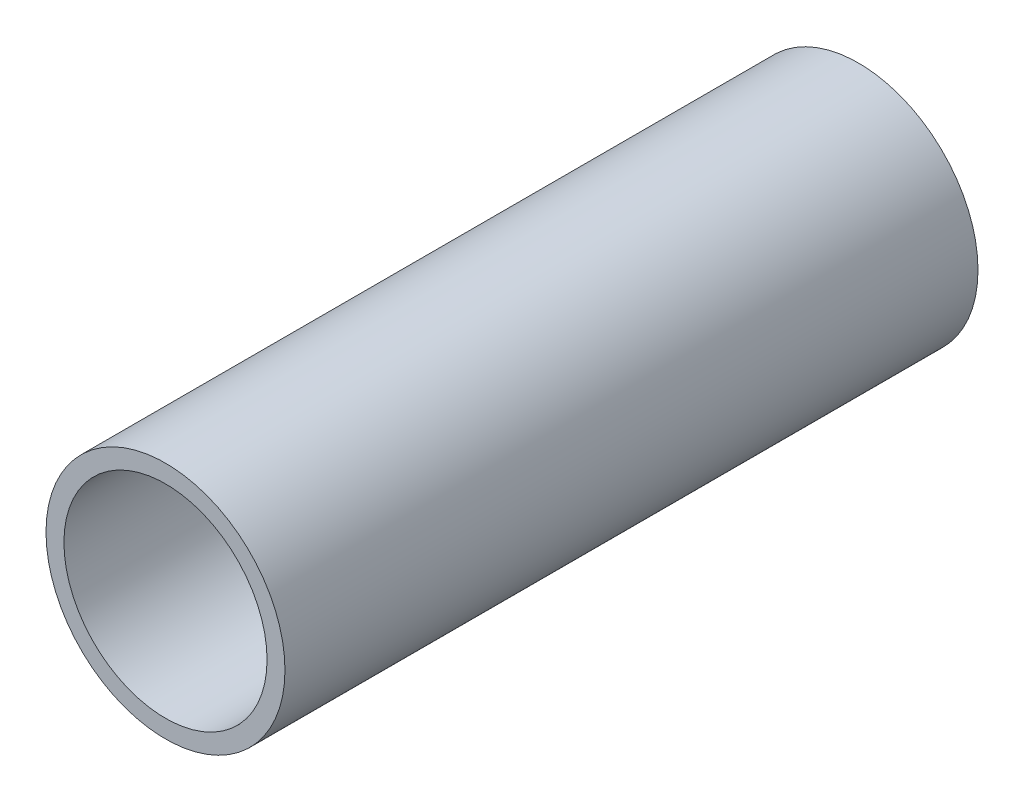
SolidWorks part; units mm, degrees
ref_plane "Front Plane" through (0, 0, 0) normal (0, 0, 1) x (1, 0, 0)
ref_plane "Top Plane" through (0, 0, 0) normal (0, 1, 0) x (1, 0, 0)
ref_plane "Right Plane" through (0, 0, 0) normal (1, 0, 0) x (0, 0, -1)
sketch "Sketch1" plane through (0, 0, 0) normal (0, 0, 1) x (1, 0, 0)
  circle A0 centre (0, 0) radius 8.5
  circle A1 centre (0, 0) radius 10
  dimension "D1" = 17
  dimension "D2" = 20
extrude "Boss-Extrude1" add sketch "Sketch1" along normal blind 58
